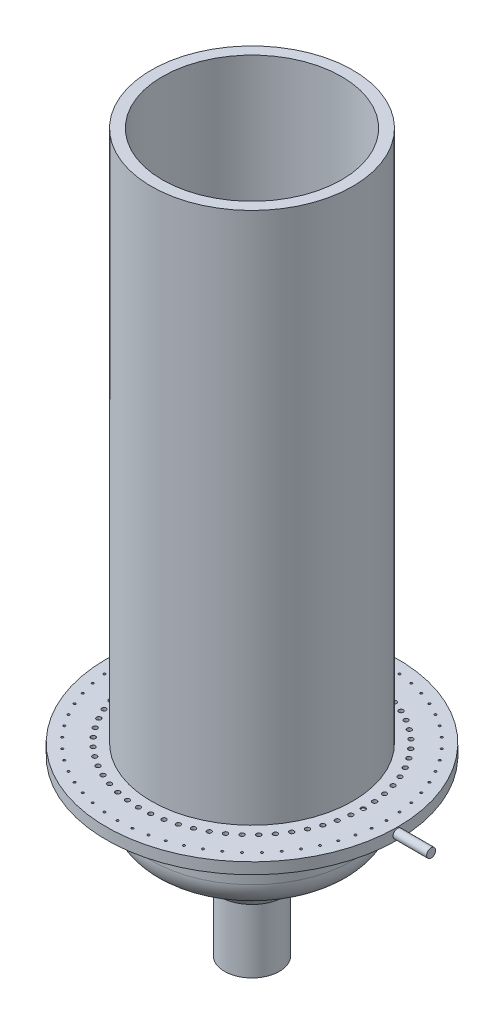
SolidWorks part; units mm, degrees
ref_plane "Front Plane" through (0, 0, 0) normal (0, 0, 1) x (1, 0, 0)
ref_plane "Top Plane" through (0, 0, 0) normal (0, 1, 0) x (1, 0, 0)
ref_plane "Right Plane" through (0, 0, 0) normal (1, 0, 0) x (0, 0, -1)
sketch "Sketch1" plane through (0, 0, 0) normal (0, 0, 1) x (1, 0, 0)
  line L0 (0, -777.6582) -> (0, 38105.2507) construction
  line L1 (-20, 8.5) -> (-20, 80)
  line L4 (20, 80) -> (20, 0)
  line L6 (-22.5, 6) -> (-22.5, 15)
  line L8 (20, 0) -> (22.5, 0)
  line L9 (22.5, 0) -> (22.5, 15)
  line L10 (-20, 80) -> (-20, 81.382)
  line L12 (20, 80) -> (20, 81.382)
  line L13 (-22.5, 15) -> (-32.5, 15)
  line L14 (-32.5, 15) -> (-32.5, 17.5)
  line L15 (-32.5, 17.5) -> (-22.5, 17.5)
  line L16 (32.5, 15) -> (32.5, 17.5)
  line L17 (32.5, 17.5) -> (22.5, 17.5)
  line L18 (22.5, 15) -> (32.5, 15)
  line L19 (-22.5, 17.5) -> (-22.5, 81.382)
  line L20 (22.5, 17.5) -> (22.5, 81.382)
  line L21 (-16.5, 0) -> (-15.2533, 0)
  line L22 (-9.8867, -3.3167) -> (-7.2361, -8.618)
  line L23 (-14, 2.5) -> (-13.7082, 2.5)
  line L24 (-8.3416, -0.8167) -> (-5, -7.5)
  line L25 (-7.2361, -8.618) -> (-6.118, -8.618)
  line L26 (-5, -8.618) -> (-5, -7.5)
  line L27 (-22.5, 81.382) -> (-22.5, 136.382)
  line L28 (-20, 81.382) -> (-20, 136.382)
  line L29 (20, 81.382) -> (20, 136.382)
  line L30 (22.5, 81.382) -> (22.5, 136.382)
  line L31 (-22.5, 136.382) -> (-20, 136.382)
  line L32 (22.5, 136.382) -> (20, 136.382)
  line L33 (-20, 0) -> (-11.5451, 0) construction
  line L34 (-20, 2.5) -> (-10, 2.5) construction
  line L35 (-10, 2.5) -> (-5, -7.5) construction
  line L36 (-11.5451, 0) -> (-7.2361, -8.618) construction
  line L39 (-20, 8.5) -> (-20, 2.5)
  line L40 (-20, 2.5) -> (-13.7082, 2.5)
  line L41 (-6.118, -8.618) -> (-6.118, -23.618)
  line L42 (-6.118, -23.618) -> (-5, -23.618)
  line L43 (-5, -23.618) -> (-5, -8.618)
  arc A0 (-22.5, 6) -> (-16.5, 0) centre (-16.5, 6) ccw
  arc A2 (-13.7082, 2.5) -> (-8.3416, -0.8167) centre (-13.7082, -3.5) cw
  arc A3 (-9.8867, -3.3167) -> (-15.2533, 0) centre (-15.2533, -6) ccw
  point P37 (-20, 2.5)
  point P45 (-20, 2.5)
  dimension "D4" = 6
  dimension "D13" = 6
  dimension "D6" = 15
  dimension "D2" = 20
  dimension "D3" = 2.5
  dimension "D5" = 10
  dimension "D7" = 10
  dimension "D8" = 2.5
  dimension "D9" = 2.5
  dimension "D10" = 90
  dimension "D12" = 55
revolve "Revolve1" add sketch "Sketch1" angle 360 about L0
sketch "Sketch3" plane through (0, 0, 0) normal (0, -1, 0) x (1, 0, 0)
  line L0 (0, 22.5) -> (0, -22.5) construction
  line L1 (-22.5, 0) -> (22.5, 0) construction
  line L2 (-18.7083, 1.25) -> (-13.9893, 1.25)
  line L3 (18.7083, 1.25) -> (13.9893, 1.25)
  line L4 (-1.25, 18.7083) -> (-1.25, 13.9893)
  line L5 (1.25, 18.7083) -> (1.25, 13.9893)
  line L6 (18.7083, -1.25) -> (13.9893, -1.25)
  line L7 (-18.7083, -1.25) -> (-13.9893, -1.25)
  line L8 (-1.25, -18.7083) -> (-1.25, -13.9893)
  line L9 (1.25, -18.7083) -> (1.25, -13.9893)
  circle A0 centre (0, 0) radius 22.5 construction
  circle A1 centre (0, 0) radius 22.5 construction
  arc A2 (-18.7083, -1.25) -> (-1.25, -18.7083) centre (0, 0) ccw
  arc A3 (-13.9893, -1.25) -> (-1.25, -13.9893) centre (0, 0) ccw
  circle A4 centre (0, 0) radius 11.5451 construction
  arc A5 (1.25, -13.9893) -> (13.9893, -1.25) centre (0, 0) ccw
  arc A6 (1.25, -18.7083) -> (18.7083, -1.25) centre (0, 0) ccw
  arc A7 (13.9893, 1.25) -> (1.25, 13.9893) centre (0, 0) ccw
  arc A8 (18.7083, 1.25) -> (1.25, 18.7083) centre (0, 0) ccw
  arc A9 (-1.25, 18.7083) -> (-18.7083, 1.25) centre (0, 0) ccw
  arc A10 (-1.25, 13.9893) -> (-13.9893, 1.25) centre (0, 0) ccw
  dimension "D1" = 37.5
  dimension "D2" = 2.5
  dimension "D3" = 1.25
  dimension "D5" = 14.0451
  dimension "D4" = 2.5
extrude "Cut-Extrude1" cut sketch "Sketch3" against normal blind 23 and the other way blind 18
sketch "Sketch4" plane through (0, 15, 0) normal (0, -1, 0) x (1, 0, 0)
  circle A0 centre (0, 0) radius 27.5 construction
  circle A1 centre (-30, 0) radius 0.25
  circle A2 centre (-25, 2.3785) radius 0.5
  circle A3 centre (0, 30) radius 0.25
  circle A4 centre (2.3785, 25) radius 0.5
  circle A5 centre (0, 0) radius 27.5 construction
  circle A6 centre (30, 0) radius 0.25
  circle A7 centre (25, -2.3785) radius 0.5
  circle A8 centre (0, 0) radius 27.5 construction
  circle A9 centre (0, -30) radius 0.25
  circle A10 centre (-2.3785, -25) radius 0.5
  circle A11 centre (0, 0) radius 27.5 construction
  point P25 (0, 0)
  dimension "D3" = 55
  dimension "D4" = 0.5
  dimension "D5" = 1
  dimension "D1" = 30
  dimension "D2" = 25
  dimension "D6" = 4
extrude "Cut-Extrude2" cut sketch "Sketch4" against normal blind 10 contours A7 | A1 | A2 | A4 | A3 | A6 | A9 | A10
pattern_circular "CirPattern1" count 15 over 360 about axis through (0, 0, 0) along (0, 1, 0) of "Cut-Extrude2"
sketch "Sketch5" plane through (0, 0, 0) normal (1, 0, 0) x (0, 0, -1)
  line L0 (32.5, 17.5) -> (-32.5, 17.5) construction
  line L1 (-6.118, -23.618) -> (6.118, -23.618) construction
  circle A0 centre (0, 16.25) radius 1
  dimension "D2" = 2
  dimension "D1" = 1.25
extrude "Boss-Extrude1" add sketch "Sketch5" along normal blind 20 from offset 20
sketch "Sketch6" plane through (0, 2.5, 0) normal (0, 1, 0) x (1, 0, 0)
  circle A0 centre (0, 0) radius 14.0451
  circle A1 centre (0, 0) radius 13.7082
extrude "Boss-Extrude2" add sketch "Sketch6" along normal blind 2
